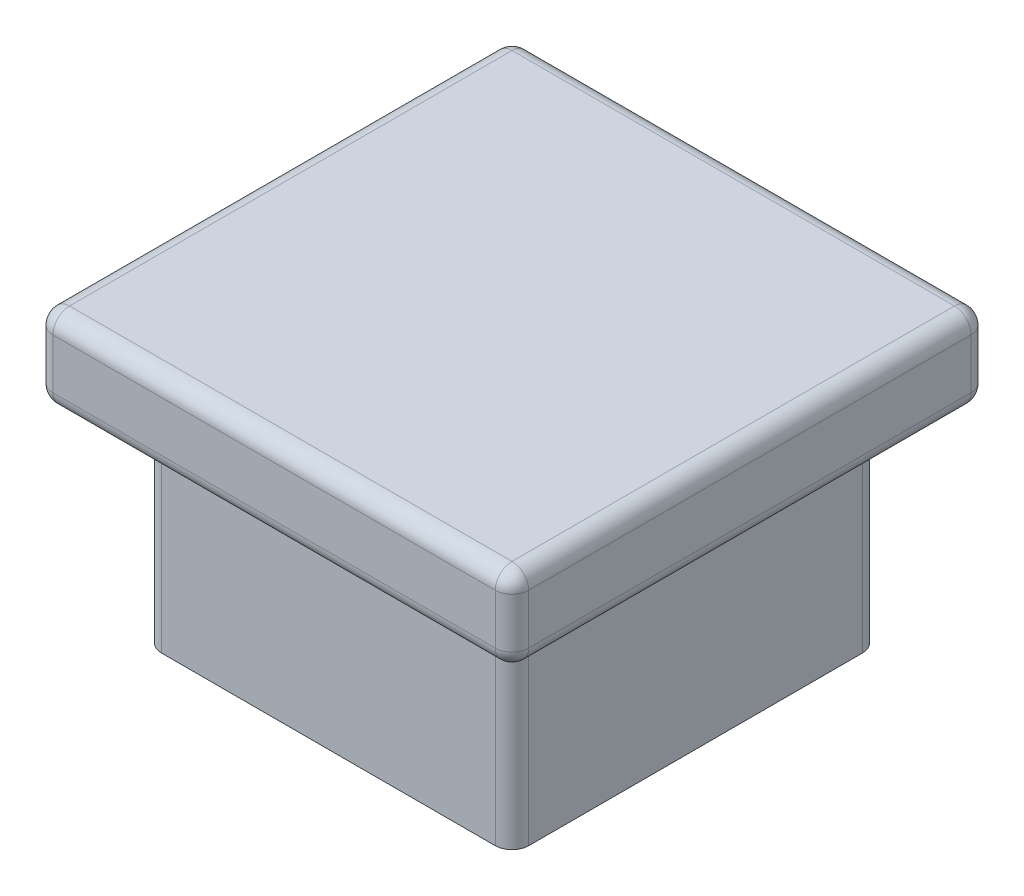
SolidWorks part; units mm, degrees
ref_plane "Front Plane" through (0, 0, 0) normal (0, 0, 1) x (1, 0, 0)
ref_plane "Top Plane" through (0, 0, 0) normal (0, 1, 0) x (1, 0, 0)
ref_plane "Right Plane" through (0, 0, 0) normal (1, 0, 0) x (0, 0, -1)
sketch "Sketch1" plane through (0, 0, 0) normal (0, 1, 0) x (1, 0, 0)
  line L1 (-19, -19) -> (19, -19)
  line L2 (-19, -19) -> (-19, 19)
  line L3 (-19, 19) -> (19, 19)
  line L4 (19, -19) -> (19, 19)
  line L5 (-19, -19) -> (19, 19) construction
  line L6 (-19, 19) -> (19, -19) construction
  line L7 (-22, -22) -> (22, -22)
  line L8 (-22, -22) -> (-22, 22)
  line L9 (-22, 22) -> (22, 22)
  line L10 (22, -22) -> (22, 22)
  line L11 (-22, -22) -> (22, 22) construction
  line L12 (-22, 22) -> (22, -22) construction
  point P0 (0, 0)
  point P6 (0, 0)
  dimension "D1" = 44
  dimension "D2" = 38
extrude "Boss-Extrude1" add sketch "Sketch1" along normal blind 25
sketch "Sketch2" plane through (0, 25, 0) normal (0, 1, 0) x (1, 0, 0)
  line L1 (-28.5, -28.5) -> (28.5, -28.5)
  line L2 (-28.5, -28.5) -> (-28.5, 28.5)
  line L3 (-28.5, 28.5) -> (28.5, 28.5)
  line L4 (28.5, -28.5) -> (28.5, 28.5)
  line L5 (-28.5, -28.5) -> (28.5, 28.5) construction
  line L6 (-28.5, 28.5) -> (28.5, -28.5) construction
  point P0 (0, 0)
  dimension "D1" = 57
extrude "Boss-Extrude2" add sketch "Sketch2" along normal blind 10
sketch "Sketch3" plane through (0, 25, 0) normal (0, -1, 0) x (1, 0, 0)
  line L1 (-22, -22) -> (22, -22)
  line L2 (-22, -22) -> (-22, 22)
  line L3 (-22, 22) -> (22, 22)
  line L4 (22, -22) -> (22, 22)
  line L5 (-22, -22) -> (22, 22) construction
  line L6 (-22, 22) -> (22, -22) construction
  line L7 (-25.75, -25.75) -> (25.75, -25.75)
  line L8 (-25.75, -25.75) -> (-25.75, 25.75)
  line L9 (-25.75, 25.75) -> (25.75, 25.75)
  line L10 (25.75, -25.75) -> (25.75, 25.75)
  line L11 (-25.75, -25.75) -> (25.75, 25.75) construction
  line L12 (-25.75, 25.75) -> (25.75, -25.75) construction
  point P0 (0, 0)
  point P7 (0, 0)
  dimension "D1" = 51.5
extrude "Cut-Extrude1" cut sketch "Sketch3" against normal blind 4
fillet "Fillet1" radius 2 16 edges at (0, 35, 28.5) (-28.5, 35, 0) (0, 35, -28.5) (28.5, 35, 0) (-28.5, 25, 0) (0, 25, -28.5) (28.5, 25, 0) (0, 25, 28.5) (22, 14.5, 22) (-22, 14.5, 22) (22, 14.5, -22) (-22, 14.5, -22) (-28.5, 30, -28.5) (28.5, 30, -28.5) (28.5, 30, 28.5) (-28.5, 30, 28.5)
